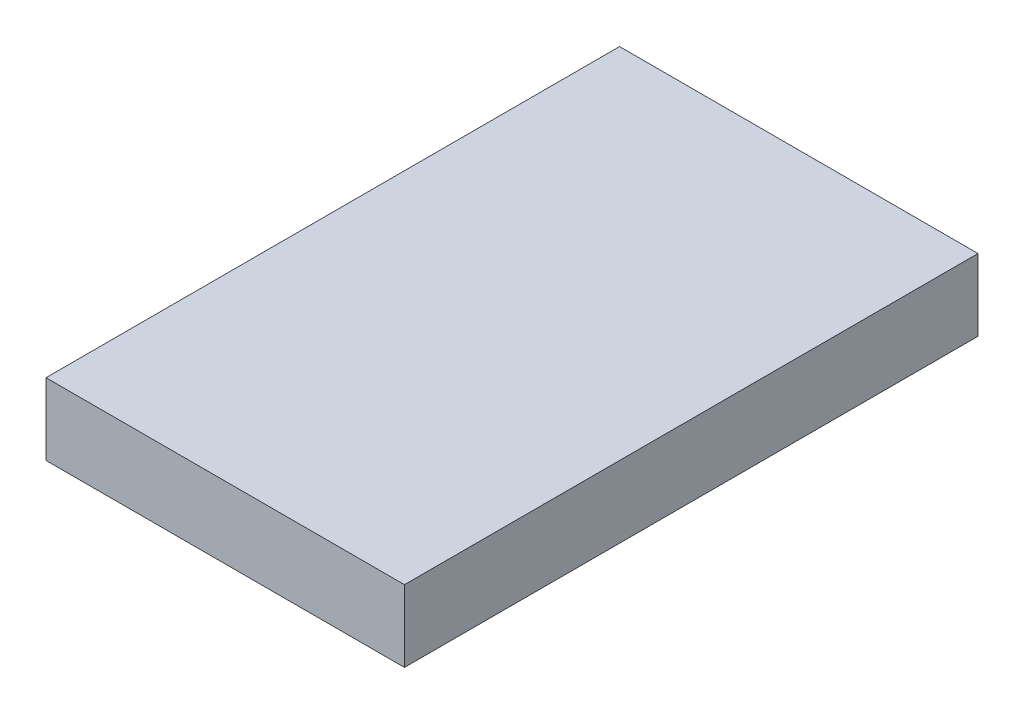
SolidWorks part; units mm, degrees
material "1060 Alloy"
ref_plane "Front Plane" through (0, 0, 0) normal (0, 0, 1) x (1, 0, 0)
ref_plane "Top Plane" through (0, 0, 0) normal (0, 1, 0) x (1, 0, 0)
ref_plane "Right Plane" through (0, 0, 0) normal (1, 0, 0) x (0, 0, -1)
sketch "Sketch1" plane through (0, 0, 0) normal (0, 1, 0) x (1, 0, 0)
  line L1 (-15, 24) -> (15, 24)
  line L2 (-15, 24) -> (-15, -24)
  line L3 (-15, -24) -> (15, -24)
  line L4 (15, 24) -> (15, -24)
  line L5 (-15, 24) -> (15, -24) construction
  line L6 (-15, -24) -> (15, 24) construction
  point P0 (0, 0)
  dimension "D1" = 48
  dimension "D2" = 30
extrude "Boss-Extrude1" add sketch "Sketch1" along normal blind 6
